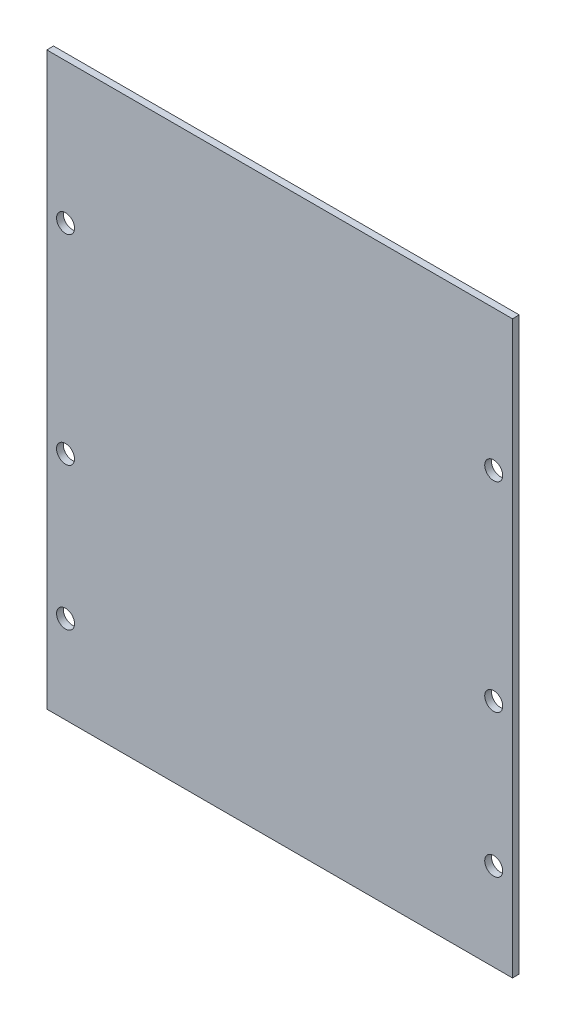
SolidWorks part; units mm, degrees
ref_plane "Front Plane" through (0, 0, 0) normal (1, 0, 0) x (0, 1, 0)
ref_plane "Top Plane" through (0, 0, 0) normal (0, 0, 1) x (0, 1, 0)
ref_plane "Right Plane" through (0, 0, 0) normal (0, 1, 0) x (-1, 0, 0)
sketch "Sketch1" plane through (0, 0, 0) normal (0, 0, 1) x (0, 1, 0)
  line L0 (32.22, 47.625) -> (32.22, -47.625) construction
  line L1 (73.5, -50.8) -> (-73.5, -50.8) construction
  line L2 (73.5, -50.8) -> (73.5, 50.8) construction
  line L3 (73.5, 50.8) -> (-73.5, 50.8) construction
  line L4 (-73.5, -50.8) -> (-73.5, 50.8) construction
  line L5 (73.5, -50.8) -> (-73.5, 50.8) construction
  line L6 (73.5, 50.8) -> (-73.5, -50.8) construction
  line L8 (63.5, -51.8) -> (-63.5, -51.8)
  line L9 (63.5, -51.8) -> (63.5, 51.8)
  line L10 (63.5, 51.8) -> (-63.5, 51.8)
  line L11 (-63.5, -51.8) -> (-63.5, 51.8)
  line L12 (63.5, -51.8) -> (-63.5, 51.8) construction
  line L13 (63.5, 51.8) -> (-63.5, -51.8) construction
  circle A0 centre (-43.98, 47.625) radius 2
  circle A1 centre (-12.23, 47.625) radius 2
  circle A2 centre (32.22, 47.625) radius 2
  circle A3 centre (-43.98, -47.625) radius 2
  circle A4 centre (-12.23, -47.625) radius 2
  circle A5 centre (32.22, -47.625) radius 2
  point P0 (0, 0)
  point P18 (32.22, 0)
  point P20 (0, 0)
  dimension "D3" = 4
  dimension "D4" = 44.45
  dimension "D1" = 101.6
  dimension "D2" = 147
  dimension "D5" = 76.2
  dimension "D6" = 95.25
  dimension "D7" = 41.28
  dimension "D8" = 1
  dimension "D9" = 10
extrude "Boss-Extrude1" add sketch "Sketch1" along normal blind 1.5
